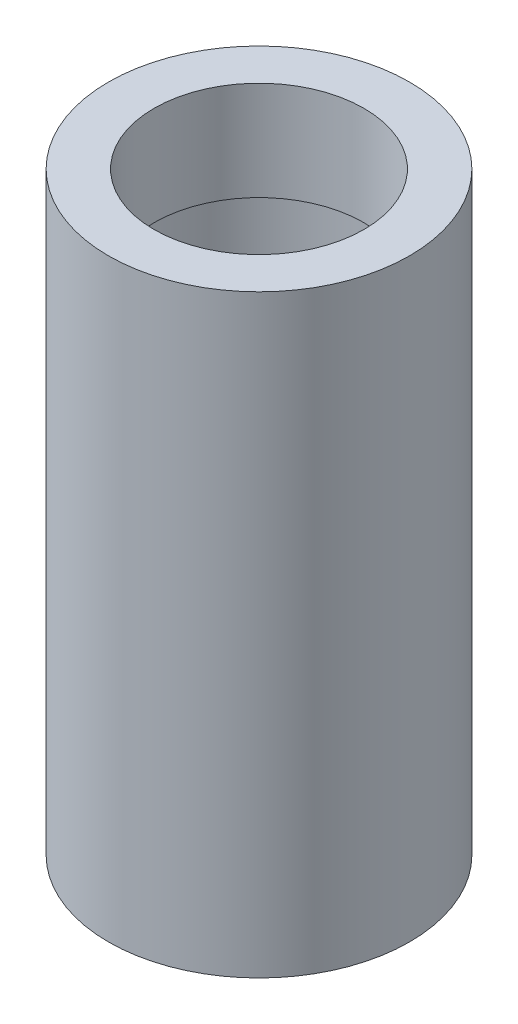
SolidWorks part; units mm, degrees
ref_plane "Alzado" through (0, 0, 0) normal (0, 0, 1) x (1, 0, 0)
ref_plane "Planta" through (0, 0, 0) normal (0, 1, 0) x (1, 0, 0)
ref_plane "Vista lateral" through (0, 0, 0) normal (1, 0, 0) x (0, 0, -1)
sketch "Croquis1" plane through (0, 0, 0) normal (0, 1, 0) x (1, 0, 0)
  circle A0 centre (0, 0) radius 3
  circle A1 centre (0, 0) radius 3.8
  dimension "D1" = 6
  dimension "D2" = 7.6
extrude "Saliente-Extruir1" add sketch "Croquis1" along normal blind 15
sketch "Croquis2" plane through (0, 15, 0) normal (0, 1, 0) x (1, 0, 0)
  circle A0 centre (0, 0) radius 3.25
  circle A1 centre (0, 0) radius 2.65
  dimension "D1" = 5.3
  dimension "D2" = 6.5
extrude "Saliente-Extruir2" add sketch "Croquis2" against normal blind 2.5
fillet "Redondeo1" radius 0.3 1 edges at (0, 0, 3)
